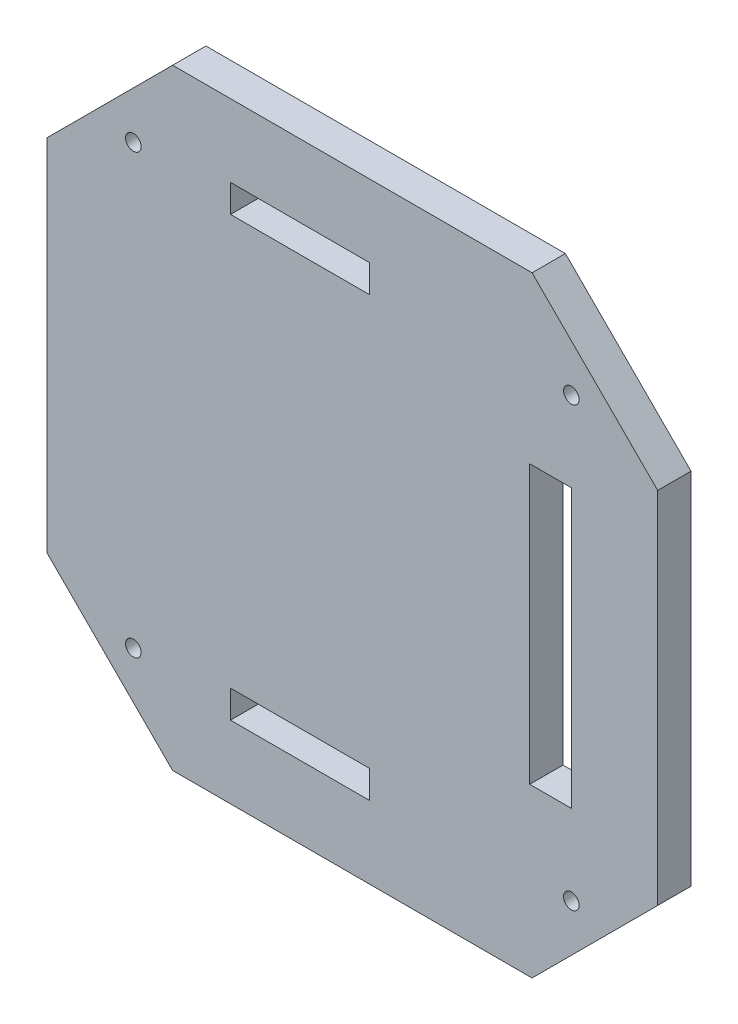
SolidWorks part; units mm, degrees
ref_plane "Plan de face" through (0, 0, 0) normal (0, 0, 1) x (1, 0, 0)
ref_plane "Plan de dessus" through (0, 0, 0) normal (0, 1, 0) x (1, 0, 0)
ref_plane "Plan de droite" through (0, 0, 0) normal (1, 0, 0) x (0, 0, -1)
sketch "Esquisse1" plane through (0, 0, -27.5) normal (0, 0, -1) x (-1, 0, 0)
  line L0 (-2.5656, -55.7278) -> (62.1796, -55.7278) construction
  line L1 (-25.193, -33.1003) -> (-2.5656, -55.7278) construction
  line L2 (-25.193, -33.1003) -> (-25.193, 31.6448) construction
  line L3 (-25.193, 31.6448) -> (-2.5656, 54.2722) construction
  line L4 (84.807, 31.6448) -> (62.1796, 54.2722) construction
  line L5 (-2.5656, 54.2722) -> (62.1796, 54.2722) construction
  line L6 (84.807, -33.1003) -> (84.807, 31.6448) construction
  line L7 (84.807, -33.1003) -> (62.1796, -55.7278) construction
  line L8 (-2.5656, -55.7278) -> (62.1796, -55.7278)
  line L9 (-25.193, -33.1003) -> (-2.5656, -55.7278)
  line L10 (-25.193, -33.1003) -> (-25.193, 31.6448)
  line L11 (-25.193, 31.6448) -> (-2.5656, 54.2722)
  line L12 (84.807, 31.6448) -> (62.1796, 54.2722)
  line L13 (-2.5656, 54.2722) -> (62.1796, 54.2722)
  line L14 (84.807, -33.1003) -> (84.807, 31.6448)
  line L15 (84.807, -33.1003) -> (62.1796, -55.7278)
  circle A0 centre (-9.6366, 38.7159) radius 1.4 construction
  circle A1 centre (69.2507, 38.7159) radius 1.4 construction
  circle A2 centre (69.2507, -40.1714) radius 1.4 construction
  circle A3 centre (-9.6366, -40.1714) radius 1.4 construction
  circle A4 centre (-9.6366, 38.7159) radius 1.4
  circle A5 centre (69.2507, 38.7159) radius 1.4
  circle A6 centre (69.2507, -40.1714) radius 1.4
  circle A7 centre (-9.6366, -40.1714) radius 1.4
extrude "Boss.-Extru.1" add sketch "Esquisse1" along normal blind 6
sketch "Esquisse2" plane through (0, 0, -33.5) normal (0, 0, -1) x (-1, 0, 0)
  circle A0 centre (69.2507, 38.7159) radius 3.25
  dimension "D1" = 6.5
extrude "Enlèv. mat.-Extru.1" cut sketch "Esquisse2" against normal blind 3
ref_plane "Plan2" through (0, -0.7278, 0) normal (0, -1, 0) x (-1, 0, 0)
ref_plane "Plan3" through (-29.807, 0, 0) normal (1, 0, 0) x (0, 0, -1)
mirror "Symétrie3" about plane through (-29.807, 0, 0) normal (1, 0, 0) of "Enlèv. mat.-Extru.1" second plane through (0, -0.7278, 0) second plane normal (0, -1, 0)
sketch "Esquisse4" plane through (0, 0, -33.5) normal (0, 0, -1) x (-1, 0, 0)
  line L0 (69.2507, -40.1714) -> (-9.6366, -40.1714) construction
  line L1 (-3.3, -0.7278) -> (3.3, -0.7278) construction
  line L2 (51.7507, -42.6714) -> (26.7507, -42.6714)
  line L3 (51.7507, -42.6714) -> (51.7507, -37.6714)
  line L4 (51.7507, -37.6714) -> (26.7507, -37.6714)
  line L5 (26.7507, -42.6714) -> (26.7507, -37.6714)
  line L6 (51.7507, -42.6714) -> (26.7507, -37.6714) construction
  line L7 (51.7507, -37.6714) -> (26.7507, -42.6714) construction
  line L8 (26.7507, 41.2159) -> (26.7507, 36.2159)
  line L9 (51.7507, 36.2159) -> (26.7507, 36.2159)
  line L10 (51.7507, 41.2159) -> (51.7507, 36.2159)
  line L11 (51.7507, 41.2159) -> (26.7507, 41.2159)
  line L12 (-9.6366, -40.1714) -> (-9.6366, 38.7159) construction
  line L14 (-9.6366, 24.2722) -> (-2.1366, 24.2722)
  line L15 (-9.6366, 24.2722) -> (-9.6366, -25.7278)
  line L16 (-9.6366, -25.7278) -> (-2.1366, -25.7278)
  line L17 (-2.1366, 24.2722) -> (-2.1366, -25.7278)
  point P4 (39.2507, -40.1714)
  point P23 (-9.6366, -0.7278)
  dimension "D1" = 5
  dimension "D2" = 25
  dimension "D3" = 30
  dimension "D4" = 50
  dimension "D5" = 7.5
extrude "Enlèv. mat.-Extru.2" cut sketch "Esquisse4" against normal through all
